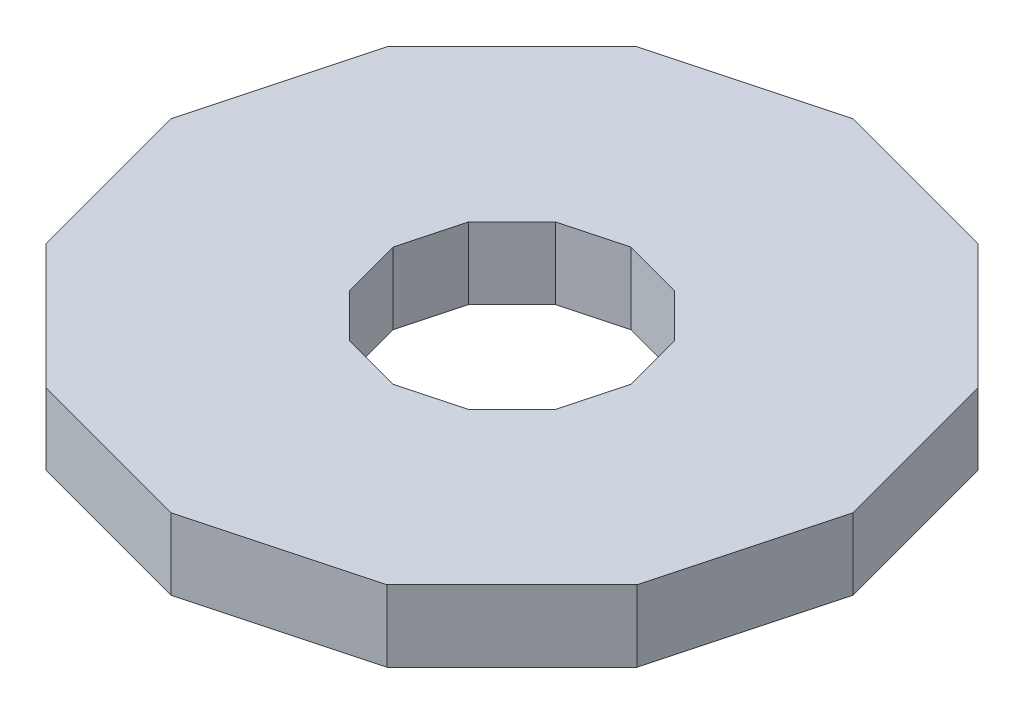
SolidWorks part; units mm, degrees
ref_plane "Front Plane" through (0, 0, 0) normal (0, 0, 1) x (1, 0, 0)
ref_plane "Top Plane" through (0, 0, 0) normal (0, 1, 0) x (1, 0, 0)
ref_plane "Right Plane" through (0, 0, 0) normal (1, 0, 0) x (0, 0, -1)
sketch "Sketch1" plane through (0, 0, 0) normal (0, 1, 0) x (1, 0, 0)
  line L0 (0, 0) -> (31.6117, 0) construction
  line L1 (90.7777, 0) -> (78.6158, 45.3889)
  line L2 (78.6158, 45.3889) -> (45.3889, 78.6158)
  line L3 (45.3889, 78.6158) -> (0, 90.7777)
  line L4 (0, 90.7777) -> (-45.3889, 78.6158)
  line L5 (-45.3889, 78.6158) -> (-78.6158, 45.3889)
  line L6 (-78.6158, 45.3889) -> (-90.7777, 0)
  line L7 (-90.7777, 0) -> (-78.6158, -45.3889)
  line L8 (-78.6158, -45.3889) -> (-45.3889, -78.6158)
  line L9 (-45.3889, -78.6158) -> (0, -90.7777)
  line L10 (0, -90.7777) -> (45.3889, -78.6158)
  line L11 (45.3889, -78.6158) -> (78.6158, -45.3889)
  line L12 (78.6158, -45.3889) -> (90.7777, 0)
  line L13 (31.6117, 0) -> (27.3765, 15.8058)
  line L14 (27.3765, 15.8058) -> (15.8058, 27.3765)
  line L15 (15.8058, 27.3765) -> (0, 31.6117)
  line L16 (0, 31.6117) -> (-15.8058, 27.3765)
  line L17 (-15.8058, 27.3765) -> (-27.3765, 15.8058)
  line L18 (-27.3765, 15.8058) -> (-31.6117, 0)
  line L19 (-31.6117, 0) -> (-27.3765, -15.8058)
  line L20 (-27.3765, -15.8058) -> (-15.8058, -27.3765)
  line L21 (-15.8058, -27.3765) -> (0, -31.6117)
  line L22 (0, -31.6117) -> (15.8058, -27.3765)
  line L23 (15.8058, -27.3765) -> (27.3765, -15.8058)
  line L24 (27.3765, -15.8058) -> (31.6117, 0)
  circle A0 centre (0, 0) radius 87.6845 construction
  circle A1 centre (0, 0) radius 30.5345 construction
  dimension "D1" = 57.15
  dimension "D2" = 46.99
extrude "Boss-Extrude1" add sketch "Sketch1" along normal blind 19.05
